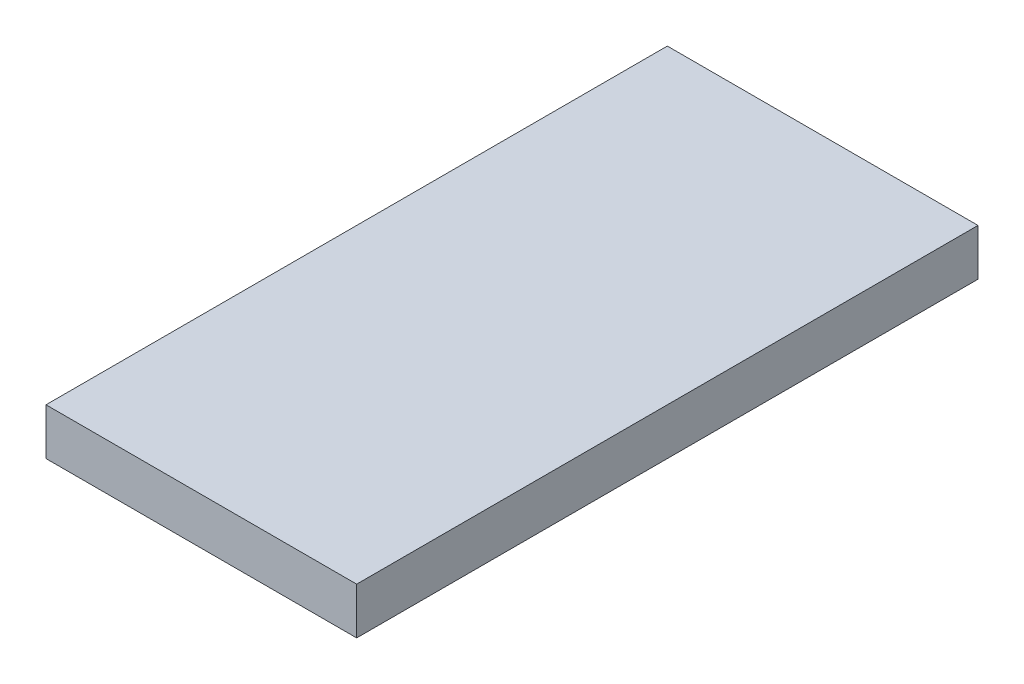
SolidWorks part; units mm, degrees
ref_plane "Front Plane" through (0, 0, 0) normal (0, 0, 1) x (1, 0, 0)
ref_plane "Top Plane" through (0, 0, 0) normal (0, 1, 0) x (1, 0, 0)
ref_plane "Right Plane" through (0, 0, 0) normal (1, 0, 0) x (0, 0, -1)
other "Configuration Table"
sketch "Sketch1" plane through (0, 0, 0) normal (0, 0, 1) x (1, 0, 0)
  line L1 (-20, 0) -> (20, 0)
  line L2 (-20, 0) -> (-20, 6)
  line L3 (-20, 6) -> (20, 6)
  line L4 (20, 0) -> (20, 6)
extrude "TEPSI_kulp_40x6x80_1" add sketch "Sketch1" along normal blind 80 from offset 160 separate body
